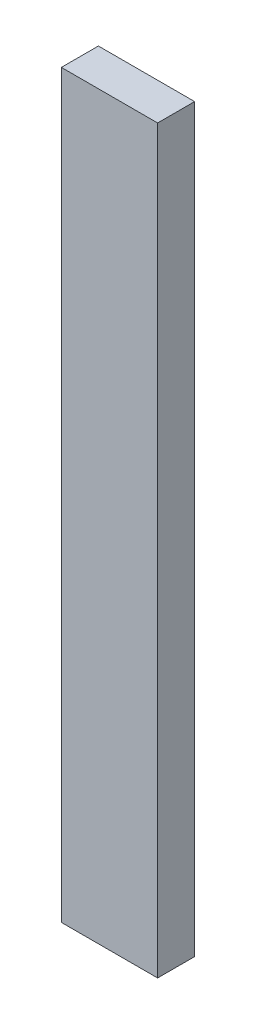
SolidWorks part; units mm, degrees
ref_plane "Front Plane" through (0, 0, 0) normal (0, 0, 1) x (1, 0, 0)
ref_plane "Top Plane" through (0, 0, 0) normal (0, 1, 0) x (1, 0, 0)
ref_plane "Right Plane" through (0, 0, 0) normal (1, 0, 0) x (0, 0, -1)
sketch "Sketch1" plane through (0, 0, 0) normal (0, 0, 1) x (1, 0, 0)
  line L1 (0, 0) -> (260, 0)
  line L2 (0, 0) -> (0, 2000)
  line L3 (0, 2000) -> (260, 2000)
  line L4 (260, 0) -> (260, 2000)
  dimension "D1" = 260
  dimension "D2" = 2000
extrude "Boss-Extrude1" add sketch "Sketch1" along normal blind 100
